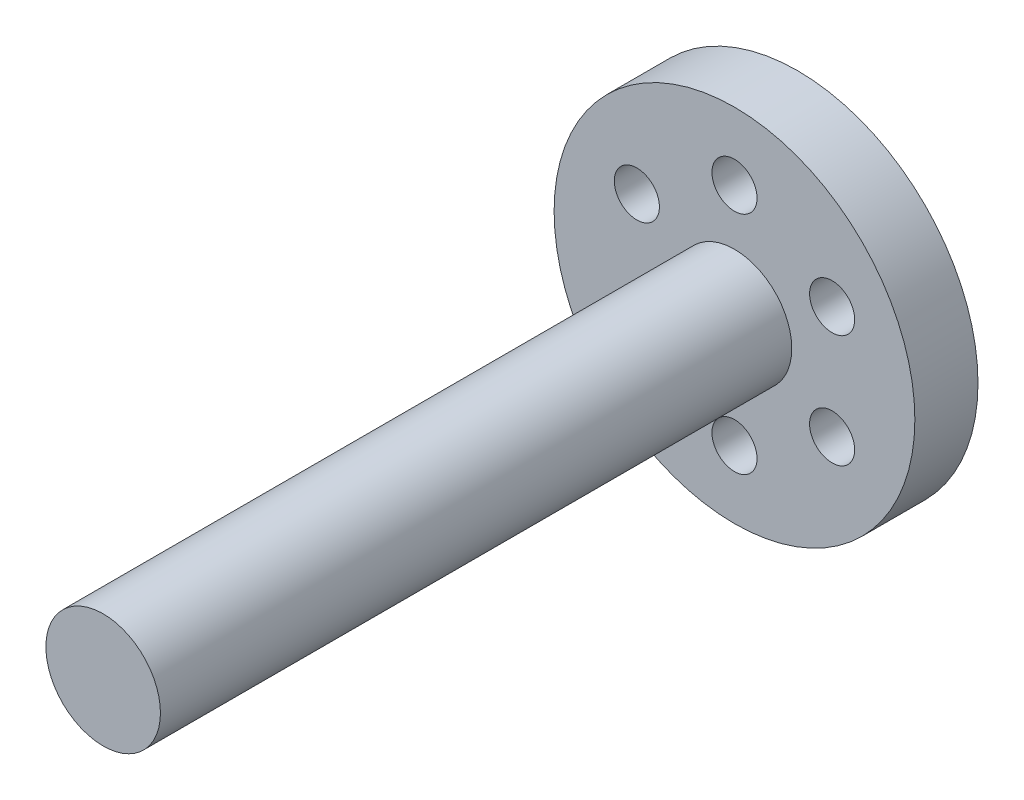
SolidWorks part; units mm, degrees
ref_plane "Alzado" through (0, 0, 0) normal (0, 0, 1) x (1, 0, 0)
ref_plane "Planta" through (0, 0, 0) normal (0, 1, 0) x (1, 0, 0)
ref_plane "Vista lateral" through (0, 0, 0) normal (1, 0, 0) x (0, 0, -1)
sketch "Sketch1" plane through (0, 0, 0) normal (0, 0, 1) x (1, 0, 0)
  circle A0 centre (0, 0) radius 20
  dimension "D1" = 40
extrude "Boss-Extrude1" add sketch "Sketch1" along normal blind 7
sketch "Sketch3" plane through (0, 0, 7) normal (0, 0, 1) x (1, 0, 0)
  circle A0 centre (0, 0) radius 6.35
  dimension "D1" = 12.7
sketch "Sketch4" plane through (0, 0, 7) normal (0, 0, 1) x (1, 0, 0)
  circle A0 centre (0, 0) radius 12.5 construction
  dimension "D1" = 25
hole_wizard "Tap Drill for M6x1.0 Tap1" positions "Sketch5" profile "Sketch6" hole size "M6x1.0" standard "ANSI Metric" end condition through all
sketch "Sketch5" plane through (0, 0, 7) normal (0, 0, 1) x (1, 0, 0)
  circle A0 centre (0, 0) radius 12.5 construction
  point P0 (0, 12.5)
sketch "Sketch6" plane through (0, 12.5, 7) normal (1, 0, 0) x (0, -1, 0)
  line L0 (0, 0) -> (0, 7)
  line L1 (0, 7) -> (2.5, 7)
  line L2 (2.5, 7) -> (2.5, 0)
  line L5 (2.5, 0) -> (0, 0)
  line L11 (0, -6.35) -> (0, 107.95) construction
  dimension "Thru Hole Dia." = 5
  dimension "Thru Hole Depth" = 7
pattern_circular "CirPattern1" count 6 over 360 about axis through (0, 0, 0) along (0, 0, 1) of "Tap Drill for M6x1.0 Tap1"
extrude "Boss-Extrude2" add sketch "Sketch3" along normal blind 70 contours A0
